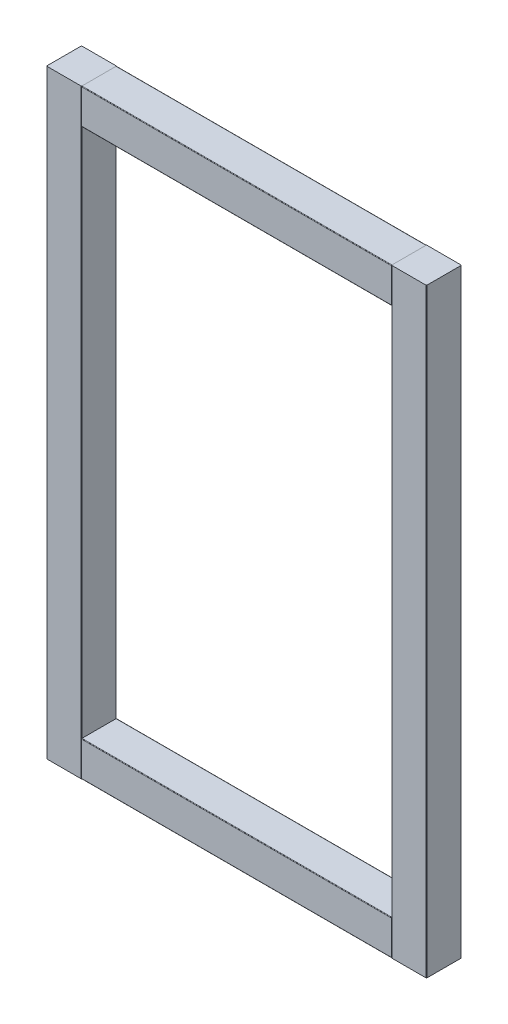
SolidWorks part; units mm, degrees
material "Pin"
ref_plane "Plan de face" through (0, 0, 0) normal (0, 0, 1) x (1, 0, 0)
ref_plane "Plan de dessus" through (0, 0, 0) normal (0, 1, 0) x (1, 0, 0)
ref_plane "Plan de droite" through (0, 0, 0) normal (1, 0, 0) x (0, 0, -1)
sketch "Esquisse1" plane through (0, 0, 0) normal (0, 0, 1) x (1, 0, 0)
  line L1 (172.5, -282.5) -> (-172.5, -282.5)
  line L2 (172.5, -282.5) -> (172.5, 282.5)
  line L3 (172.5, 282.5) -> (-172.5, 282.5)
  line L4 (-172.5, -282.5) -> (-172.5, 282.5)
  line L5 (172.5, -282.5) -> (-172.5, 282.5) construction
  line L6 (172.5, 282.5) -> (-172.5, -282.5) construction
  point P0 (0, 0)
  dimension "D1" = 345
  dimension "D2" = 565
other "Custom TASSEAU-CARRE-33(1)"
ref_plane "Plan1" through (172.5, -282.5, 0) normal (0, 1, 0) x (-1, 0, 0)
sketch "Esquisse14" plane through (172.5, -282.5, 0) normal (0, 1, 0) x (-1, 0, 0)
  line L5 (-15, -15) -> (15, 15) construction
  line L6 (-15, 15) -> (15, -15) construction
  line L7 (-17, -17.5) -> (17, -17.5)
  line L8 (-17.5, -17) -> (-17.5, 17)
  line L9 (-17, 17.5) -> (17, 17.5)
  line L10 (17.5, -17) -> (17.5, 17)
  line L11 (-17.5, -17.5) -> (17.5, 17.5) construction
  line L12 (-17.5, 17.5) -> (17.5, -17.5) construction
  arc A0 (17, -17.5) -> (17.5, -17) centre (17, -17) ccw
  arc A3 (-17, -17.5) -> (-17.5, -17) centre (-17, -17) cw
  arc A4 (17, 17.5) -> (17.5, 17) centre (17, 17) cw
  arc A7 (-17.5, 17) -> (-17, 17.5) centre (-17, 17) cw
  point P0 (0, 0)
  point P6 (0, 0)
  point P14 (0, 0)
  point P35 (0, 17.5)
  point P36 (0, 15)
  point P37 (-15, 0)
  point P38 (-17.5, 0)
  point P39 (0, -15)
  point P40 (0, -17.5)
  point P41 (15, 0)
  point P42 (17.5, 0)
  dimension "D5" = 0.5
  dimension "D1" = 0.5
  dimension "D4" = 0.5
  dimension "D2" = 35
  dimension "D3" = 35
